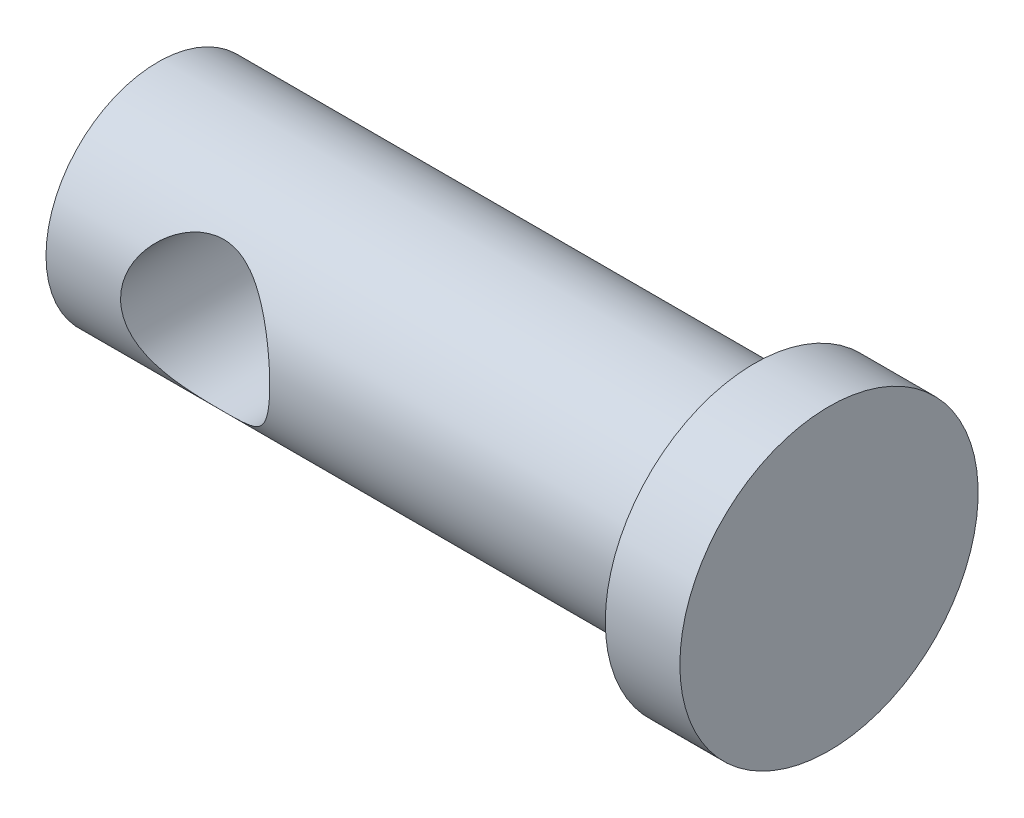
SolidWorks part; units mm, degrees
material "Brass"
ref_plane "Front Plane" through (0, 0, 0) normal (0, 0, 1) x (1, 0, 0)
ref_plane "Top Plane" through (0, 0, 0) normal (0, 1, 0) x (1, 0, 0)
ref_plane "Right Plane" through (0, 0, 0) normal (1, 0, 0) x (0, 0, -1)
sketch "Sketch1" plane through (0, 0, 0) normal (0, 0, 1) x (1, 0, 0)
  line L0 (0, 2) -> (-1, 2)
  line L1 (-1, 2) -> (-1, 1.5)
  line L2 (-1, 1.5) -> (-9, 1.5)
  line L3 (-9, 1.5) -> (-9, 0)
  line L4 (-9, 0) -> (0, 0)
  line L5 (0, 0) -> (0, 2)
  dimension "D1" = 2
  dimension "D2" = 1.5
  dimension "D3" = 8
  dimension "D4" = 1
revolve "Revolve1" add sketch "Sketch1" angle 360 about L4
sketch "Sketch2" plane through (0, 0, 0) normal (0, 0, 1) x (1, 0, 0)
  line L0 (-9, 1.5) -> (-9, -1.5) construction
  circle A0 centre (-7, 0) radius 1
  dimension "D1" = 2
  dimension "D2" = 2
extrude "Cut-Extrude1" cut sketch "Sketch2" against normal through all both and the other way through all contours A0
